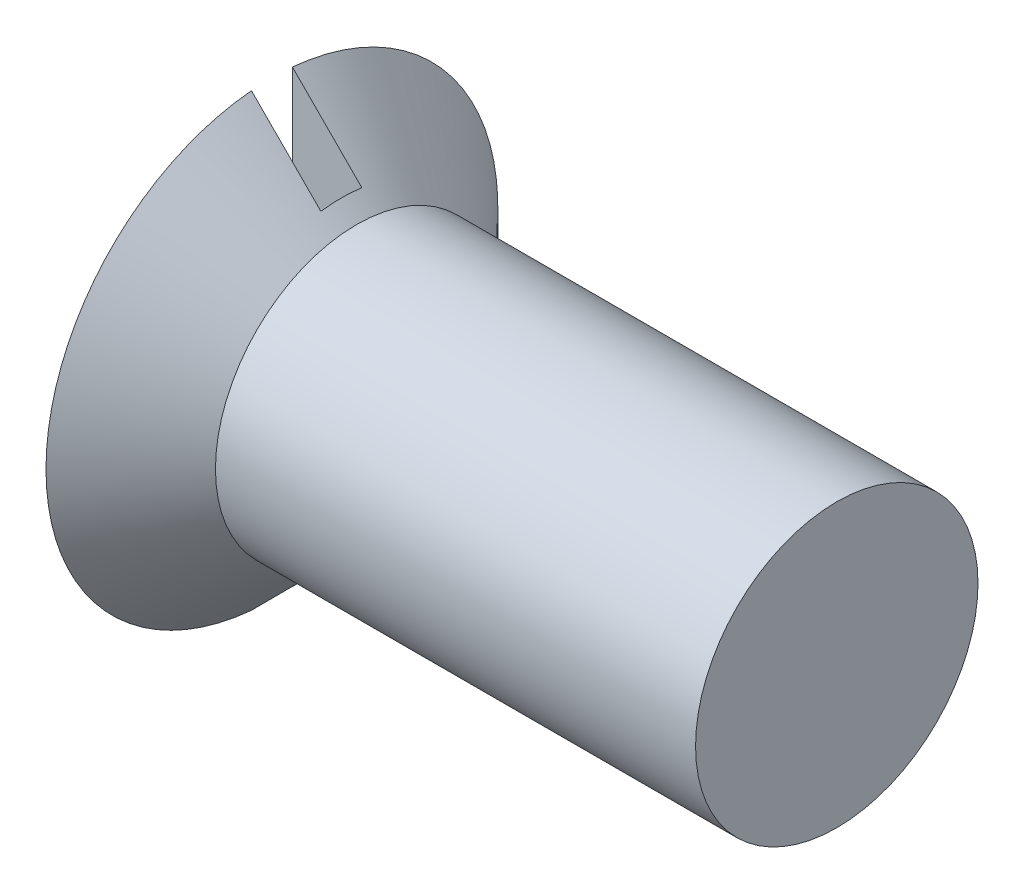
SolidWorks part; units mm, degrees
ref_plane "Front Plane" through (0, 0, 0) normal (0, 0, 1) x (1, 0, 0)
ref_plane "Top Plane" through (0, 0, 0) normal (0, 1, 0) x (1, 0, 0)
ref_plane "Right Plane" through (0, 0, 0) normal (1, 0, 0) x (0, 0, -1)
sketch "Sketch1" plane through (0, 0, 0) normal (0, 0, 1) x (1, 0, 0)
  line L0 (0, 0) -> (12.7, 0)
  line L1 (12.7, 0) -> (12.7, 3.175)
  line L2 (12.7, 3.175) -> (1.905, 3.175)
  line L3 (1.905, 3.175) -> (0, 5.08)
  line L4 (0, 0) -> (0, -3.5825) construction
  line L5 (0, 5.08) -> (0, 0)
  dimension "D1" = 5.08
  dimension "D2" = 3.175
  dimension "D3" = 12.7
  dimension "D4" = 45
revolve "Revolve1" add sketch "Sketch1" angle 360 about L0
sketch "Sketch2" plane through (0, 0, 0) normal (0, 1, 0) x (1, 0, 0)
  line L1 (-1.5596, 0.4604) -> (1.5596, 0.4604)
  line L2 (-1.5596, 0.4604) -> (-1.5596, -0.4604)
  line L3 (-1.5596, -0.4604) -> (1.5596, -0.4604)
  line L4 (1.5596, 0.4604) -> (1.5596, -0.4604)
  line L5 (-1.5596, 0.4604) -> (1.5596, -0.4604) construction
  line L6 (-1.5596, -0.4604) -> (1.5596, 0.4604) construction
  point P0 (0, 0)
extrude "Cut-Extrude1" cut sketch "Sketch2" against normal mid plane 15.748
